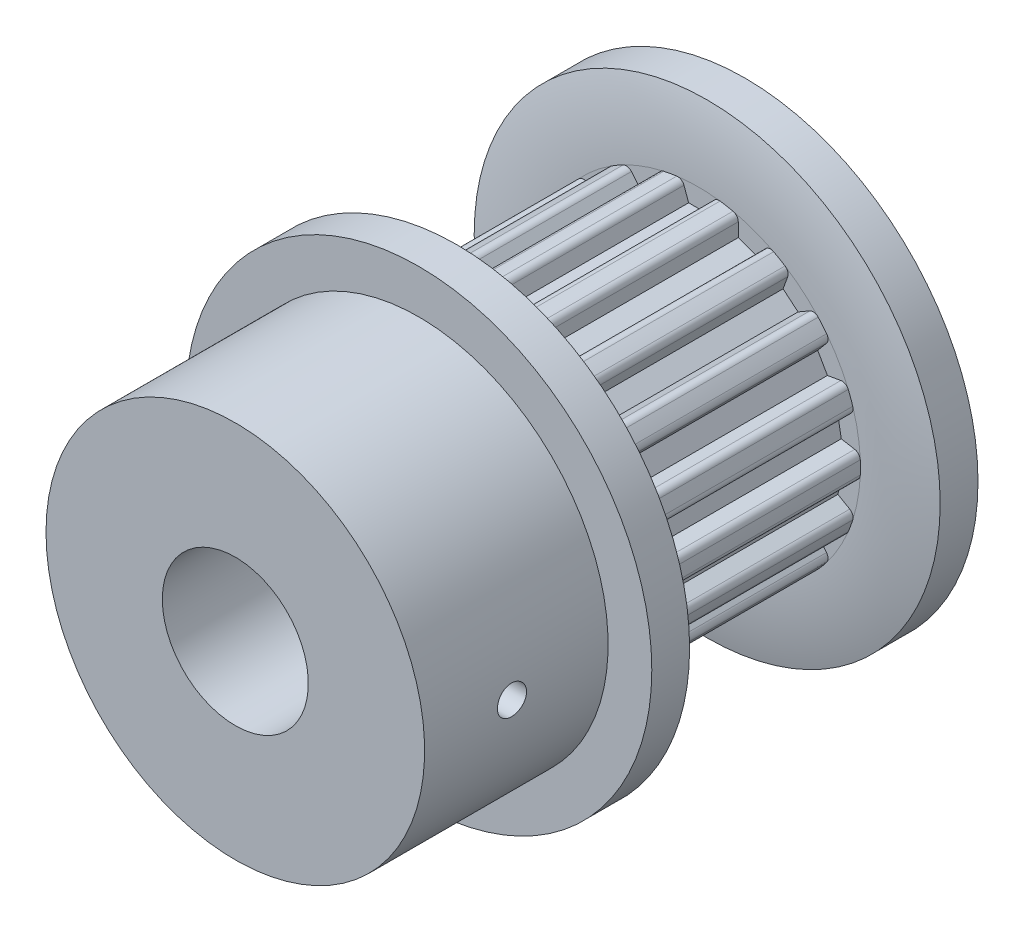
SolidWorks part; units mm, degrees
ref_plane "Front Plane" through (0, 0, 0) normal (0, 0, 1) x (1, 0, 0)
ref_plane "Top Plane" through (0, 0, 0) normal (0, 1, 0) x (1, 0, 0)
ref_plane "Right Plane" through (0, 0, 0) normal (1, 0, 0) x (0, 0, -1)
sketch "Sketch8" plane through (0, 0, 0) normal (1, 0, 0) x (0, 0, -1)
  line L0 (7.5979, 0) -> (-14.162, 0) construction
  line L1 (5.6, -2.5063) -> (5.6, -8)
  line L2 (4, -5.5625) -> (-4, -5.5625)
  line L4 (5.6, -8) -> (4.3016, -8)
  line L6 (-4.3016, -8) -> (-5.6, -8)
  line L8 (-5.6, -8) -> (-5.6, -6.5)
  line L10 (-5.6, -6.5) -> (-11.9, -6.5)
  line L12 (-11.9, -6.5) -> (-11.9, -2.5063)
  line L13 (5.6, -2.5063) -> (-11.9, -2.5063)
  arc A0 (4.3016, -8) -> (4, -5.5625) centre (14, -5.5625) cw
  arc A2 (-4.3016, -8) -> (-4, -5.5625) centre (-14, -5.5625) ccw
  dimension "D1" = 2.5063
revolve "Revolve1" add sketch "Sketch8" angle 360 about L0
sketch "Sketch7" plane through (0, 0, 0) normal (0, 0, 1) x (1, 0, 0)
  line L0 (-1.9984, 4.5111) -> (-1.3688, 4.7402)
  line L4 (-1.3688, 4.7402) -> (-1.3688, 5.2095)
  line L5 (-1.9984, 4.5111) -> (-2.3, 4.8705)
  line L7 (-0.335, 4.9225) -> (0.335, 4.9225)
  line L9 (0.335, 4.9225) -> (0.4955, 5.3635)
  line L11 (-0.335, 4.9225) -> (-0.4955, 5.3635)
  line L12 (1.3688, 4.7402) -> (1.9984, 4.5111)
  line L13 (1.9984, 4.5111) -> (2.3, 4.8705)
  line L14 (1.3688, 4.7402) -> (1.3688, 5.2095)
  line L15 (2.9075, 3.9862) -> (3.4207, 3.5555)
  line L16 (3.4207, 3.5555) -> (3.8271, 3.7902)
  line L17 (2.9075, 3.9862) -> (3.068, 4.4272)
  line L18 (4.0955, 2.7514) -> (4.4305, 2.1711)
  line L19 (4.4305, 2.1711) -> (4.8926, 2.2526)
  line L20 (4.0955, 2.7514) -> (4.3971, 3.1108)
  line L21 (4.7895, 1.1847) -> (4.9059, 0.5249)
  line L22 (4.9059, 0.5249) -> (5.368, 0.4434)
  line L23 (4.7895, 1.1847) -> (5.1959, 1.4193)
  line L24 (4.9059, -0.5249) -> (4.7895, -1.1847)
  line L25 (4.7895, -1.1847) -> (5.1959, -1.4193)
  line L26 (4.9059, -0.5249) -> (5.368, -0.4434)
  line L27 (4.4305, -2.1711) -> (4.0955, -2.7514)
  line L28 (4.0955, -2.7514) -> (4.3971, -3.1108)
  line L29 (4.4305, -2.1711) -> (4.8926, -2.2526)
  line L30 (3.4207, -3.5555) -> (2.9075, -3.9862)
  line L31 (2.9075, -3.9862) -> (3.068, -4.4272)
  line L32 (3.4207, -3.5555) -> (3.8271, -3.7902)
  line L33 (1.9984, -4.5111) -> (1.3688, -4.7402)
  line L34 (1.3688, -4.7402) -> (1.3688, -5.2095)
  line L35 (1.9984, -4.5111) -> (2.3, -4.8705)
  line L36 (0.335, -4.9225) -> (-0.335, -4.9225)
  line L37 (-0.335, -4.9225) -> (-0.4955, -5.3635)
  line L38 (0.335, -4.9225) -> (0.4955, -5.3635)
  line L39 (-1.3688, -4.7402) -> (-1.9984, -4.5111)
  line L40 (-1.9984, -4.5111) -> (-2.3, -4.8705)
  line L41 (-1.3688, -4.7402) -> (-1.3688, -5.2095)
  line L42 (-2.9075, -3.9862) -> (-3.4207, -3.5555)
  line L43 (-3.4207, -3.5555) -> (-3.8271, -3.7902)
  line L44 (-2.9075, -3.9862) -> (-3.068, -4.4272)
  line L45 (-4.0955, -2.7514) -> (-4.4305, -2.1711)
  line L46 (-4.4305, -2.1711) -> (-4.8926, -2.2526)
  line L47 (-4.0955, -2.7514) -> (-4.3971, -3.1108)
  line L48 (-4.7895, -1.1847) -> (-4.9059, -0.5249)
  line L49 (-4.9059, -0.5249) -> (-5.368, -0.4434)
  line L50 (-4.7895, -1.1847) -> (-5.1959, -1.4193)
  line L51 (-4.9059, 0.5249) -> (-4.7895, 1.1847)
  line L52 (-4.7895, 1.1847) -> (-5.1959, 1.4193)
  line L53 (-4.9059, 0.5249) -> (-5.368, 0.4434)
  line L54 (-4.4305, 2.1711) -> (-4.0955, 2.7514)
  line L55 (-4.0955, 2.7514) -> (-4.3971, 3.1108)
  line L56 (-4.4305, 2.1711) -> (-4.8926, 2.2526)
  line L57 (-3.4207, 3.5555) -> (-2.9075, 3.9862)
  line L58 (-2.9075, 3.9862) -> (-3.068, 4.4272)
  line L59 (-3.4207, 3.5555) -> (-3.8271, 3.7902)
  arc A0 (0.7423, 5.5127) -> (0.4955, 5.3635) centre (0.7116, 5.2848) ccw
  arc A2 (-1.1879, 5.4342) -> (-1.3688, 5.2095) centre (-1.1388, 5.2095) ccw
  arc A3 (-2.3, 4.8705) -> (-2.583, 4.9264) centre (-2.4762, 4.7227) ccw
  arc A4 (-0.4955, 5.3635) -> (-0.7423, 5.5127) centre (-0.7116, 5.2848) ccw
  arc A6 (0.7423, 5.5127) -> (-0.7423, 5.5127) centre (0, 0) ccw
  arc A7 (2.583, 4.9264) -> (2.3, 4.8705) centre (2.4762, 4.7227) ccw
  arc A8 (-1.1879, 5.4342) -> (-2.583, 4.9264) centre (0, 0) ccw
  arc A9 (1.3688, 5.2095) -> (1.1879, 5.4342) centre (1.1388, 5.2095) ccw
  arc A10 (2.583, 4.9264) -> (1.1879, 5.4342) centre (0, 0) ccw
  arc A11 (4.1122, 3.7459) -> (3.8271, 3.7902) centre (3.9421, 3.591) ccw
  arc A12 (3.068, 4.4272) -> (2.9749, 4.7002) centre (2.8519, 4.5058) ccw
  arc A13 (4.1122, 3.7459) -> (2.9749, 4.7002) centre (0, 0) ccw
  arc A14 (5.1453, 2.1135) -> (4.8926, 2.2526) centre (4.9326, 2.0261) ccw
  arc A15 (4.3971, 3.1108) -> (4.403, 3.3992) centre (4.221, 3.2587) ccw
  arc A16 (5.1453, 2.1135) -> (4.403, 3.3992) centre (0, 0) ccw
  arc A17 (5.5579, 0.2262) -> (5.368, 0.4434) centre (5.3281, 0.2169) ccw
  arc A18 (5.1959, 1.4193) -> (5.3001, 1.6883) centre (5.0809, 1.6185) ccw
  arc A19 (5.5579, 0.2262) -> (5.3001, 1.6883) centre (0, 0) ccw
  arc A20 (5.3001, -1.6883) -> (5.1959, -1.4193) centre (5.0809, -1.6185) ccw
  arc A21 (5.368, -0.4434) -> (5.5579, -0.2262) centre (5.3281, -0.2169) ccw
  arc A22 (5.3001, -1.6883) -> (5.5579, -0.2262) centre (0, 0) ccw
  arc A23 (4.403, -3.3992) -> (4.3971, -3.1108) centre (4.221, -3.2587) ccw
  arc A24 (4.8926, -2.2526) -> (5.1453, -2.1135) centre (4.9326, -2.0261) ccw
  arc A25 (4.403, -3.3992) -> (5.1453, -2.1135) centre (0, 0) ccw
  arc A26 (2.9749, -4.7002) -> (3.068, -4.4272) centre (2.8519, -4.5058) ccw
  arc A27 (3.8271, -3.7902) -> (4.1122, -3.7459) centre (3.9421, -3.591) ccw
  arc A28 (2.9749, -4.7002) -> (4.1122, -3.7459) centre (0, 0) ccw
  arc A29 (1.1879, -5.4342) -> (1.3688, -5.2095) centre (1.1388, -5.2095) ccw
  arc A30 (2.3, -4.8705) -> (2.583, -4.9264) centre (2.4762, -4.7227) ccw
  arc A31 (1.1879, -5.4342) -> (2.583, -4.9264) centre (0, 0) ccw
  arc A32 (-0.7423, -5.5127) -> (-0.4955, -5.3635) centre (-0.7116, -5.2848) ccw
  arc A33 (0.4955, -5.3635) -> (0.7423, -5.5127) centre (0.7116, -5.2848) ccw
  arc A34 (-0.7423, -5.5127) -> (0.7423, -5.5127) centre (0, 0) ccw
  arc A35 (-2.583, -4.9264) -> (-2.3, -4.8705) centre (-2.4762, -4.7227) ccw
  arc A36 (-1.3688, -5.2095) -> (-1.1879, -5.4342) centre (-1.1388, -5.2095) ccw
  arc A37 (-2.583, -4.9264) -> (-1.1879, -5.4342) centre (0, 0) ccw
  arc A38 (-4.1122, -3.7459) -> (-3.8271, -3.7902) centre (-3.9421, -3.591) ccw
  arc A39 (-3.068, -4.4272) -> (-2.9749, -4.7002) centre (-2.8519, -4.5058) ccw
  arc A40 (-4.1122, -3.7459) -> (-2.9749, -4.7002) centre (0, 0) ccw
  arc A41 (-5.1453, -2.1135) -> (-4.8926, -2.2526) centre (-4.9326, -2.0261) ccw
  arc A42 (-4.3971, -3.1108) -> (-4.403, -3.3992) centre (-4.221, -3.2587) ccw
  arc A43 (-5.1453, -2.1135) -> (-4.403, -3.3992) centre (0, 0) ccw
  arc A44 (-5.5579, -0.2262) -> (-5.368, -0.4434) centre (-5.3281, -0.2169) ccw
  arc A45 (-5.1959, -1.4193) -> (-5.3001, -1.6883) centre (-5.0809, -1.6185) ccw
  arc A46 (-5.5579, -0.2262) -> (-5.3001, -1.6883) centre (0, 0) ccw
  arc A47 (-5.3001, 1.6883) -> (-5.1959, 1.4193) centre (-5.0809, 1.6185) ccw
  arc A48 (-5.368, 0.4434) -> (-5.5579, 0.2262) centre (-5.3281, 0.2169) ccw
  arc A49 (-5.3001, 1.6883) -> (-5.5579, 0.2262) centre (0, 0) ccw
  arc A50 (-4.403, 3.3992) -> (-4.3971, 3.1108) centre (-4.221, 3.2587) ccw
  arc A51 (-4.8926, 2.2526) -> (-5.1453, 2.1135) centre (-4.9326, 2.0261) ccw
  arc A52 (-4.403, 3.3992) -> (-5.1453, 2.1135) centre (0, 0) ccw
  arc A53 (-2.9749, 4.7002) -> (-3.068, 4.4272) centre (-2.8519, 4.5058) ccw
  arc A54 (-3.8271, 3.7902) -> (-4.1122, 3.7459) centre (-3.9421, 3.591) ccw
  arc A55 (-2.9749, 4.7002) -> (-4.1122, 3.7459) centre (0, 0) ccw
  point P152 (0, 0)
  dimension "D1" = 18
extrude "Cut-Extrude1" cut sketch "Sketch7" against normal blind 4 and the other way blind 4
hole_wizard "Ø1.0 (1) Diameter Hole1" positions "3DSketch1" profile "Sketch6" hole size "Ø1.0" standard "ANSI Metric"
sketch3d "3DSketch1"
  point P0 (6.5, 0, 8.9)
sketch "Sketch6" plane through (6.5, 0, 8.9) normal (0, 1, 0) x (0, 0, -1)
  line L0 (0, 0) -> (0, 3.9937)
  line L1 (0, 3.9937) -> (0.5, 3.9937)
  line L2 (0.5, 3.9937) -> (0.5, 0)
  line L5 (0.5, 0) -> (0, 0)
  line L11 (0, -6.35) -> (0, 107.95) construction
  dimension "Thru Hole Dia." = 1
  dimension "Thru Hole Depth" = 3.9937
